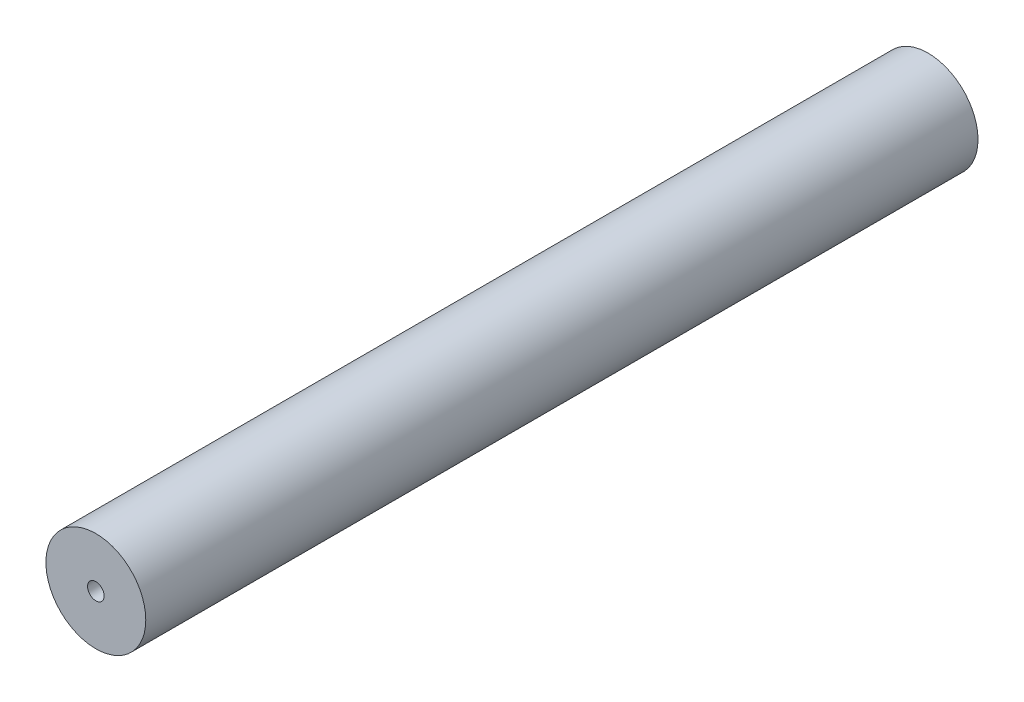
SolidWorks part; units mm, degrees
ref_plane "Plan de face" through (0, 0, 0) normal (0, 0, 1) x (1, 0, 0)
ref_plane "Plan de dessus" through (0, 0, 0) normal (0, 1, 0) x (1, 0, 0)
ref_plane "Plan de droite" through (0, 0, 0) normal (1, 0, 0) x (0, 0, -1)
sketch "Esquisse1" plane through (0, 0, 0) normal (0, 0, 1) x (1, 0, 0)
  circle A0 centre (0, 0) radius 30
  circle A1 centre (0, 0) radius 5
  dimension "D1" = 60
  dimension "D2" = 10
extrude "Boss.-Extru.1" add sketch "Esquisse1" along normal blind 500
